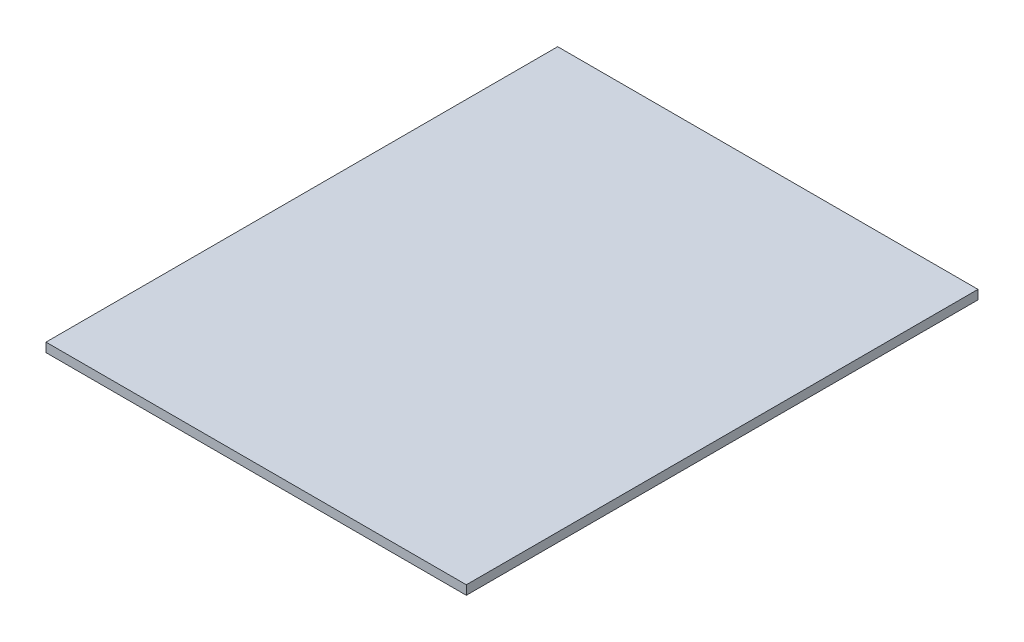
SolidWorks part; units mm, degrees
ref_plane "Front Plane" through (0, 0, 0) normal (0, 0, 1) x (1, 0, 0)
ref_plane "Top Plane" through (0, 0, 0) normal (0, 1, 0) x (1, 0, 0)
ref_plane "Right Plane" through (0, 0, 0) normal (1, 0, 0) x (0, 0, -1)
sketch "Sketch2" plane through (0, 0, 0) normal (0, 1, 0) x (1, 0, 0)
  line L0 (217.6576, 278.8941) -> (222.7076, 278.8941) construction
  line L1 (-6.2227, -1.1059) -> (223.7773, -1.1059)
  line L2 (-6.2227, -1.1059) -> (-6.2227, 278.8941)
  line L3 (-6.2227, 278.8941) -> (223.7773, 278.8941)
  line L4 (223.7773, -1.1059) -> (223.7773, 278.8941)
  line L5 (-0.2424, 278.8941) -> (-5.2924, 278.8941) construction
  point P4 (222, 272.61)
  point P5 (222, 272.61)
  point P7 (222, 272.61)
  point P8 (0, 0)
  point P9 (223.942, 274.777)
  point P10 (222.3771, 278.8941)
  point P13 (223.7246, 278.8941)
  point P14 (-6.2924, 278.8941)
  point P15 (-6.2924, 6.2841)
  point P16 (223.7076, 6.2841)
  point P17 (-1.2148, 278.8941)
  dimension "D1" = 280
  dimension "D2" = 230
extrude "Boss-Extrude1" add sketch "Sketch2" along normal blind 5
sketch "Sketch4" [suppressed] plane through (0, 5, 0) normal (0, 1, 0) x (1, 0, 0)
  line L0 (61, 9.2084) -> (141, 9.2084)
  line L1 (0, 50.3605) -> (202, 50.3605)
  line L2 (141, 9.2084) -> (141, 83.5404)
  line L3 (141, 83.5404) -> (61, 83.5404)
  line L4 (101, 83.5404) -> (101, 17.1805) construction
  line L5 (61, 9.2084) -> (61, 83.5404)
  line L6 (0, 252.61) -> (0, 0) construction
  line L7 (202, 0) -> (202, 252.61) construction
  point P12 (101, 50.3605)
  dimension "D1" = 80
extrude "Cut-Extrude1" [suppressed] cut sketch "Sketch4" against normal blind 10
